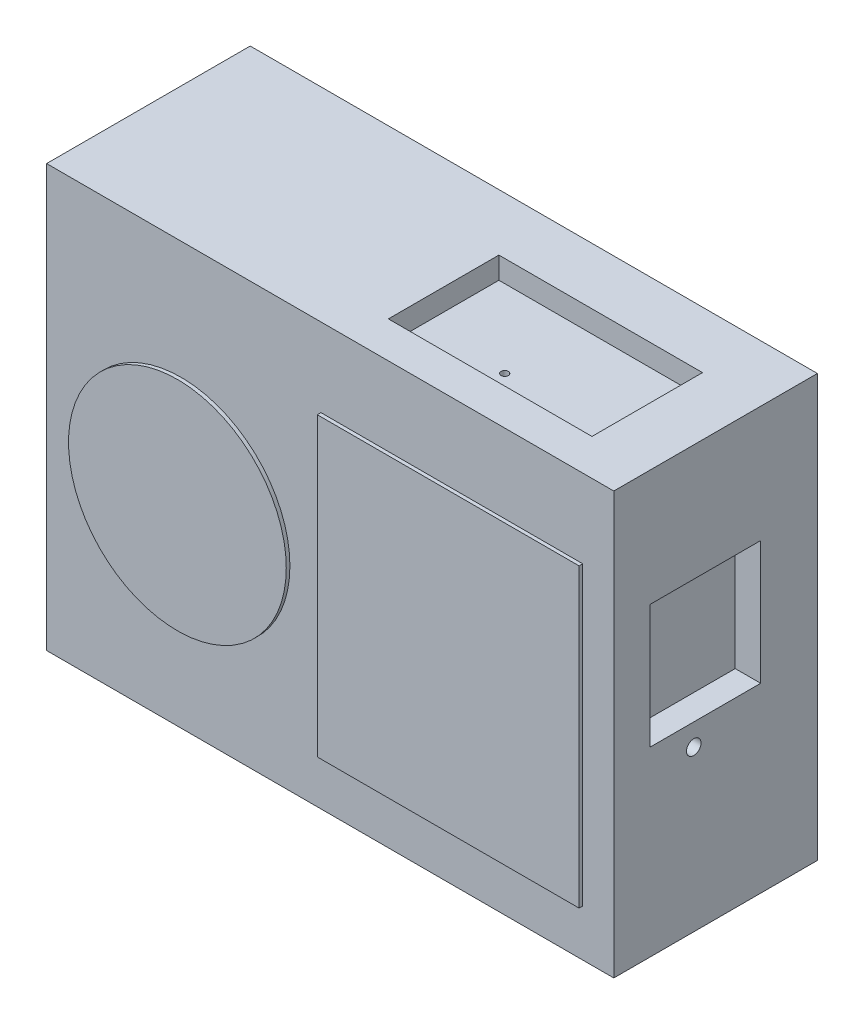
SolidWorks part; units mm, degrees
ref_plane "前视基准面" through (0, 0, 0) normal (0, 0, 1) x (1, 0, 0)
ref_plane "上视基准面" through (0, 0, 0) normal (0, 1, 0) x (1, 0, 0)
ref_plane "右视基准面" through (0, 0, 0) normal (1, 0, 0) x (0, 0, -1)
sketch "草图1" plane through (0, 0, 0) normal (0, 0, 1) x (1, 0, 0)
  line L1 (0, 0) -> (78, 0)
  line L2 (0, 0) -> (0, -58)
  line L3 (0, -58) -> (78, -58)
  line L4 (78, 0) -> (78, -58)
  dimension "D1" = 78
  dimension "D2" = 58
extrude "凸台-拉伸1" add sketch "草图1" along normal blind 28
sketch "草图2" plane through (0, 0, 0) normal (0, 1, 0) x (1, 0, 0)
  line L0 (78, -28) -> (0, -28) construction
  line L1 (42, -7.8) -> (70, -7.8)
  line L2 (42, -7.8) -> (42, -23)
  line L3 (42, -23) -> (70, -23)
  line L4 (70, -7.8) -> (70, -23)
  line L5 (78, -28) -> (78, 0) construction
  dimension "D1" = 28
  dimension "D2" = 15.2
  dimension "D3" = 5
  dimension "D4" = 8
extrude "切除-拉伸1" cut sketch "草图2" against normal blind 3
sketch "草图5" plane through (0, 0, 28) normal (0, 0, 1) x (1, 0, 0)
  line L1 (37.7218, -10.8009) -> (73.7308, -10.8009)
  line L2 (37.7218, -10.8009) -> (37.7218, -51.5618)
  line L3 (37.7218, -51.5618) -> (73.7308, -51.5618)
  line L4 (73.7308, -10.8009) -> (73.7308, -51.5618)
  circle A0 centre (18.4861, -31.1814) radius 14.9728
extrude "凸台-拉伸4" add sketch "草图5" along normal blind 0.5
sketch "草图6" plane through (0, -3, 0) normal (0, 1, 0) x (1, 0, 0)
  line L0 (42, -23) -> (70, -23) construction
  line L1 (42, -7.8) -> (42, -23) construction
  circle A0 centre (53.5, -18.5) radius 0.5
  dimension "D3" = 1
  dimension "D1" = 4.5
  dimension "D2" = 11.5
extrude "切除-拉伸2" cut sketch "草图6" against normal blind 5
sketch "草图7" plane through (78, 0, 0) normal (1, 0, 0) x (0, 0, -1)
  line L0 (-28, -58) -> (-28, 0) construction
  line L1 (-7.8, -16) -> (-23, -16)
  line L2 (-7.8, -16) -> (-7.8, -33)
  line L3 (-7.8, -33) -> (-23, -33)
  line L4 (-23, -16) -> (-23, -33)
  line L5 (-28, 0) -> (0, 0) construction
  line L6 (-28, -58) -> (0, -58) construction
  circle A0 centre (-17, -36) radius 1
  point P14 (-18.191, -35.6911)
  dimension "D5" = 2
  dimension "D7" = 11
  dimension "D1" = 15.2
  dimension "D2" = 17
  dimension "D3" = 5
  dimension "D4" = 16
  dimension "D6" = 22
extrude "切除-拉伸3" cut sketch "草图7" against normal blind 3.5
